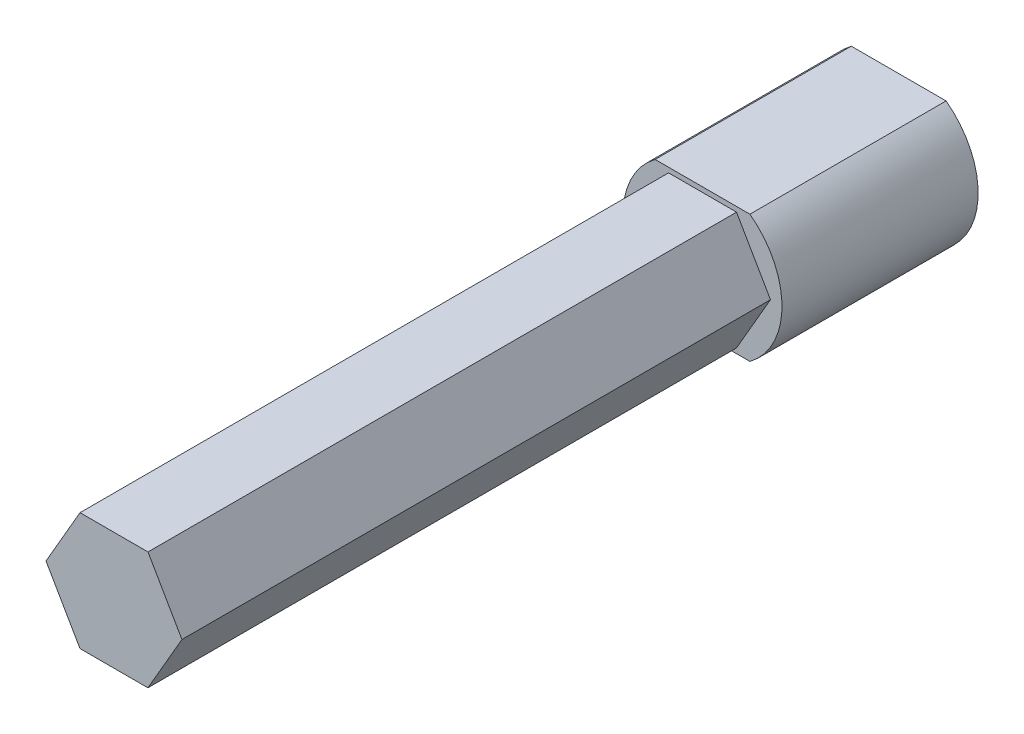
SolidWorks part; units mm, degrees
ref_plane "Front Plane" through (0, 0, 0) normal (0, 0, 1) x (1, 0, 0)
ref_plane "Top Plane" through (0, 0, 0) normal (0, 1, 0) x (1, 0, 0)
ref_plane "Right Plane" through (0, 0, 0) normal (1, 0, 0) x (0, 0, -1)
sketch "Sketch1" plane through (0, 0, 0) normal (0, 0, 1) x (1, 0, 0)
  line L0 (-2.4166, 3.25) -> (2.4166, 3.25)
  line L1 (-2.4166, -3.25) -> (2.4166, -3.25)
  arc A0 (-2.4166, 3.25) -> (-2.4166, -3.25) centre (0, 0) ccw
  arc A2 (2.4166, -3.25) -> (2.4166, 3.25) centre (0, 0) ccw
  dimension "D1" = 8.1
  dimension "D3" = 6.5
extrude "Boss-Extrude2" add sketch "Sketch1" along normal blind 10
sketch "Sketch3" plane through (0, 0, 0) normal (0, 0, -1) x (-1, 0, 0)
  line L2 (2.4166, 3.25) -> (-2.4166, 3.25)
  line L3 (-2.4166, -3.25) -> (2.4166, -3.25)
  line L4 (2.4166, 3.25) -> (-2.4166, 3.25)
  line L5 (-2.4166, -3.25) -> (2.4166, -3.25)
  line L6 (2.1909, 2.6) -> (-2.1909, 2.6)
  line L7 (-2.1909, -2.6) -> (2.1909, -2.6)
  arc A2 (2.4166, -3.25) -> (2.4166, 3.25) centre (0, 0) ccw
  arc A3 (-2.4166, 3.25) -> (-2.4166, -3.25) centre (0, 0) ccw
  arc A4 (2.4166, -3.25) -> (2.4166, 3.25) centre (0, 0) ccw
  arc A5 (-2.4166, 3.25) -> (-2.4166, -3.25) centre (0, 0) ccw
  arc A6 (-2.1909, 2.6) -> (-2.1909, -2.6) centre (0, 0) ccw
  arc A7 (2.1909, -2.6) -> (2.1909, 2.6) centre (0, 0) ccw
  dimension "D1" = 0
  dimension "D3" = 0.65
sketch "Sketch4" plane through (0, 0, 10) normal (0, 0, 1) x (1, 0, 0)
  line L1 (1.7303, -3.001) -> (3.4641, -0.0021)
  line L2 (3.4641, -0.0021) -> (1.7339, 2.999)
  line L3 (1.7339, 2.999) -> (-1.7303, 3.001)
  line L4 (-1.7303, 3.001) -> (-3.4641, 0.0021)
  line L5 (-3.4641, 0.0021) -> (-1.7339, -2.999)
  line L6 (-1.7339, -2.999) -> (1.7303, -3.001)
  circle A0 centre (0, 0) radius 3 construction
  dimension "D1" = 6
extrude "Boss-Extrude3" add sketch "Sketch4" along normal blind 30
extrude "Cut-Extrude1" cut sketch "Sketch3" against normal blind 5 contours L6 A6 L7 A7
